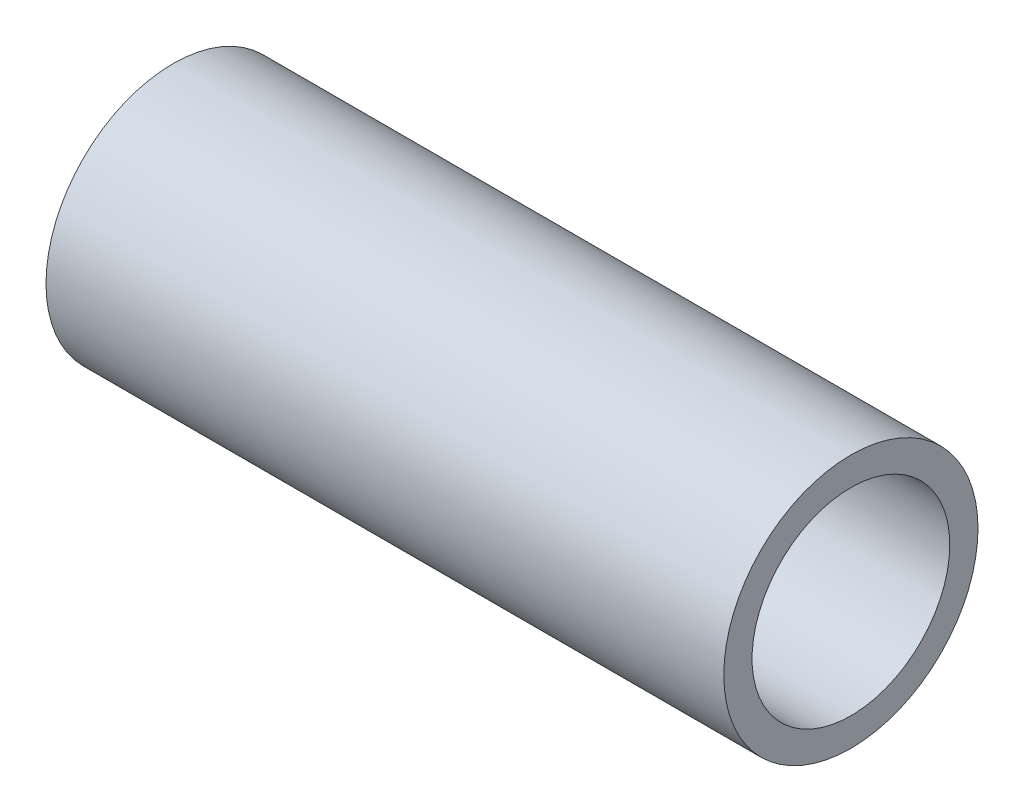
SolidWorks part; units mm, degrees
material "Gray Cast Iron"
ref_plane "Front Plane" through (0, 0, 0) normal (0, 0, 1) x (1, 0, 0)
ref_plane "Top Plane" through (0, 0, 0) normal (0, 1, 0) x (1, 0, 0)
ref_plane "Right Plane" through (0, 0, 0) normal (1, 0, 0) x (0, 0, -1)
sketch "Sketch1" plane through (0, 0, 0) normal (1, 0, 0) x (0, 0, -1)
  circle A0 centre (0, 0) radius 28
  circle A1 centre (0, 0) radius 36
  dimension "D1" = 72
  dimension "D2" = 56
extrude "Boss-Extrude1" add sketch "Sketch1" along normal mid plane 192
